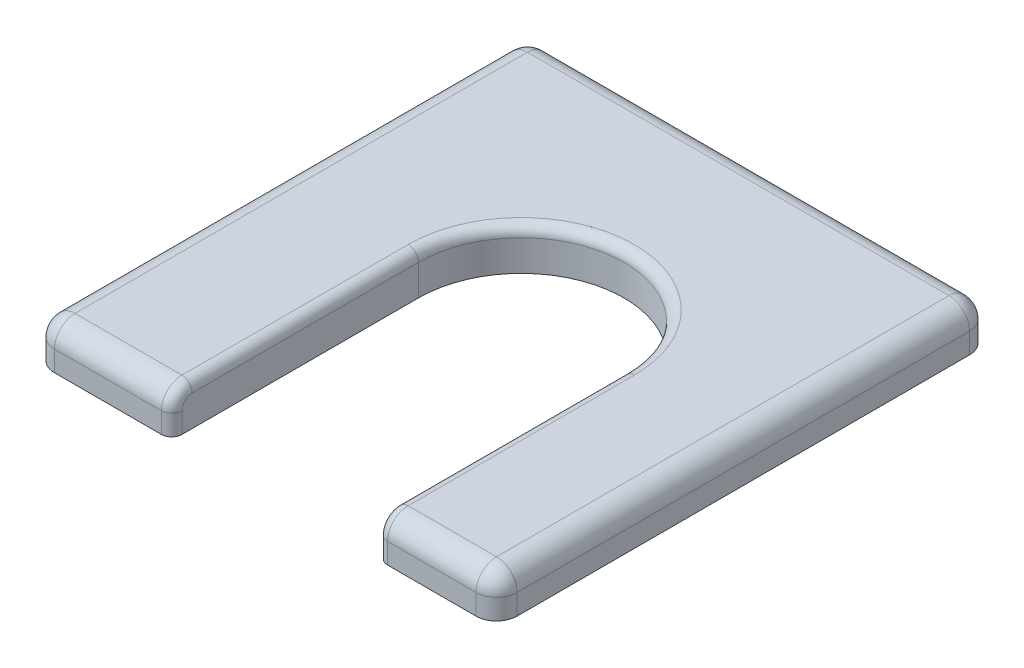
SolidWorks part; units mm, degrees
ref_plane "Front Plane" through (0, 0, 0) normal (0, 0, 1) x (1, 0, 0)
ref_plane "Top Plane" through (0, 0, 0) normal (0, 1, 0) x (1, 0, 0)
ref_plane "Right Plane" through (0, 0, 0) normal (1, 0, 0) x (0, 0, -1)
sketch "Sketch1" plane through (0, 0, 0) normal (0, 1, 0) x (1, 0, 0)
  line L1 (0, 0) -> (57.15, 0)
  line L2 (0, 0) -> (0, 60.96)
  line L3 (0, 60.96) -> (57.15, 60.96)
  line L4 (57.15, 0) -> (57.15, 60.96)
  dimension "D1" = 60.96
  dimension "D2" = 57.15
extrude "Boss-Extrude1" add sketch "Sketch1" along normal blind 5.08
fillet "Fillet1" radius 2.54 8 edges at (0, 5.08, -30.48) (0, 2.54, 0) (28.575, 5.08, 0) (57.15, 2.54, 0) (57.15, 5.08, -30.48) (28.575, 5.08, -60.96) (57.15, 2.54, -60.96) (0, 2.54, -60.96)
sketch "Sketch2" plane through (0, 5.08, 0) normal (0, 1, 0) x (1, 0, 0)
  line L0 (0, 30.48) -> (57.15, 30.48) construction
  line L2 (54.61, 0) -> (2.54, 0) construction
  line L3 (0, 2.54) -> (0, 58.42) construction
  line L6 (17.018, 30.48) -> (17.018, 0)
  line L7 (17.018, 0) -> (42.418, 0)
  line L8 (42.418, 0) -> (42.418, 30.48)
  line L9 (57.15, 58.42) -> (57.15, 2.54) construction
  arc A0 (42.418, 30.48) -> (17.018, 30.48) centre (29.718, 30.48) ccw
  point P8 (0, 0)
  dimension "D1" = 25.4
  dimension "D2" = 27.432
extrude "Cut-Extrude1" cut sketch "Sketch2" against normal up to surface (5.08 mm away) up to face at (28.575, 0, -30.48)
fillet "Fillet2" radius 1.27 7 edges at (42.418, 1.27, 0) (42.418, 4.3361, -0.7439) (42.418, 5.08, -16.51) (17.018, 1.27, 0) (17.018, 4.3361, -0.7439) (17.018, 5.08, -16.51) (29.718, 5.08, -43.18)
